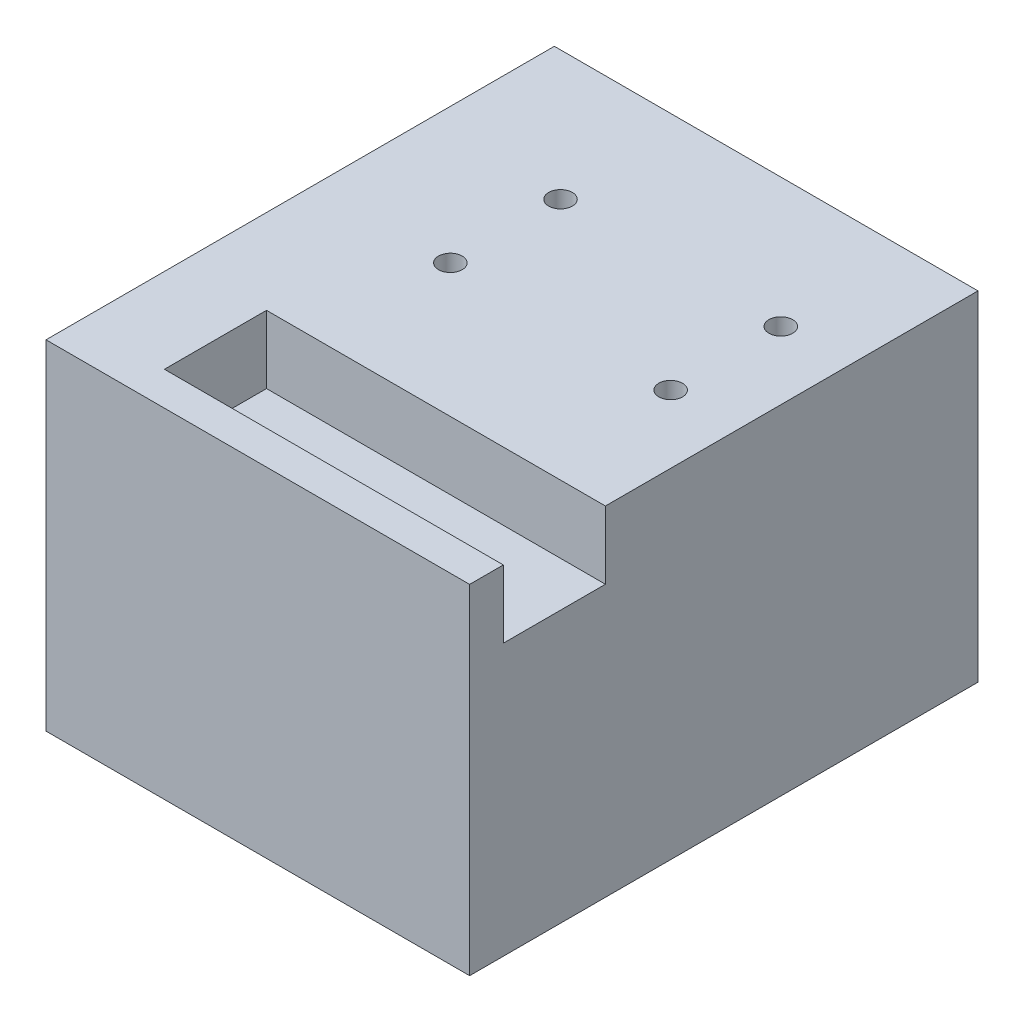
SolidWorks part; units mm, degrees
ref_plane "Front Plane" through (0, 0, 0) normal (0, 0, 1) x (1, 0, 0)
ref_plane "Top Plane" through (0, 0, 0) normal (0, 1, 0) x (1, 0, 0)
ref_plane "Right Plane" through (0, 0, 0) normal (1, 0, 0) x (0, 0, -1)
sketch "Sketch2" plane through (0, 0, 0) normal (0, 1, 0) x (1, 0, 0)
  line L1 (-40, -50) -> (40, -50)
  line L2 (-40, -50) -> (-40, 50)
  line L3 (-40, 50) -> (40, 50)
  line L4 (40, -50) -> (40, 50)
  line L5 (-40, -50) -> (40, 50) construction
  line L6 (-40, 50) -> (40, -50) construction
  point P0 (0, 0)
  dimension "D1" = 80
  dimension "D2" = 100
extrude "Boss-Extrude1" add sketch "Sketch2" along normal blind 40
sketch "Sketch3" plane through (0, 40, 0) normal (0, 1, 0) x (1, 0, 0)
  line L0 (0, 6.025) -> (0, -6.025)
  line L1 (0, -6.025) -> (40, -6.025)
  line L2 (40, -50) -> (40, 50) construction
  line L3 (40, -6.025) -> (40, 6.025)
  line L4 (40, 6.025) -> (0, 6.025)
  point P3 (0, 0)
  dimension "D1" = 12.05
extrude "Cut-Extrude1" cut sketch "Sketch3" against normal blind 8
sketch "Sketch5" plane through (0, 40, 0) normal (0, 1, 0) x (1, 0, 0)
  line L0 (40, 6.025) -> (40, 50) construction
  line L1 (0, 15.225) -> (38, 15.225)
  line L2 (0, 15.225) -> (0, 42.225)
  line L3 (0, 42.225) -> (38, 42.225)
  line L4 (38, 15.225) -> (38, 42.225)
  circle A0 centre (6, 21.725) radius 1.4
  circle A1 centre (32, 21.725) radius 1.4
  circle A2 centre (32, 34.725) radius 1.4
  circle A3 centre (6, 34.725) radius 1.4
  dimension "D7" = 2.8
  dimension "D10" = 2.8
  dimension "D11" = 2.8
  dimension "D12" = 6
  dimension "D1" = 9.2
  dimension "D2" = 38
  dimension "D3" = 27
  dimension "D4" = 2
  dimension "D5" = 6.5
  dimension "D6" = 6
  dimension "D8" = 6
  dimension "D9" = 7.5
extrude "Cut-Extrude2" cut sketch "Sketch5" against normal blind 2 contours A1 | A2 | A0 | A3
sketch "Sketch8" plane through (-40, 0, 0) normal (-1, 0, 0) x (0, 0, 1)
  line L1 (-50, 40) -> (50, 40)
  line L2 (-50, 40) -> (-50, 0)
  line L3 (-50, 0) -> (50, 0)
  line L4 (50, 40) -> (50, 0)
extrude "Cut-Extrude5" cut sketch "Sketch8" against normal blind 30
sketch "Sketch9" plane through (0, 0, 50) normal (0, 0, 1) x (1, 0, 0)
  line L1 (-10, 40) -> (40, 40)
  line L2 (-10, 40) -> (-10, 0)
  line L3 (-10, 0) -> (40, 0)
  line L4 (40, 40) -> (40, 0)
extrude "Cut-Extrude6" cut sketch "Sketch9" against normal blind 40
